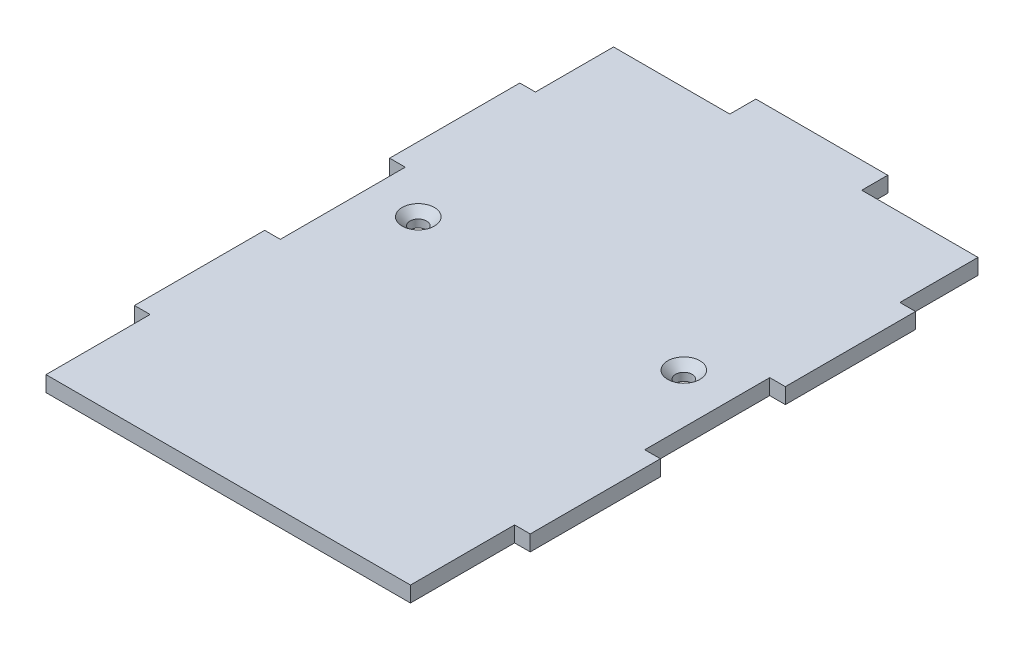
SolidWorks part; units mm, degrees
ref_plane "Front Plane" through (0, 0, 0) normal (0, 0, 1) x (1, 0, 0)
ref_plane "Top Plane" through (0, 0, 0) normal (0, 1, 0) x (1, 0, 0)
ref_plane "Right Plane" through (0, 0, 0) normal (1, 0, 0) x (0, 0, -1)
sketch "Sketch1" plane through (0, 0, 0) normal (0, 1, 0) x (1, 0, 0)
  line L0 (0, -57) -> (-35, -57)
  line L1 (-38, -57) -> (38, -57) construction
  line L2 (-38, -57) -> (-38, 57) construction
  line L3 (-38, 57) -> (38, 57) construction
  line L4 (38, -57) -> (38, 57) construction
  line L5 (0, 57) -> (0, -57)
  line L6 (-38, 0) -> (38, 0) construction
  line L7 (-35, -57) -> (-35, -37)
  line L8 (-35, -37) -> (-38, -37)
  line L9 (-38, -37) -> (-38, -12)
  line L10 (-38, -12) -> (-35, -12)
  line L11 (-35, -12) -> (-35, 12)
  line L12 (-35, 12) -> (-38, 12)
  line L13 (-38, 12) -> (-38, 37)
  line L14 (-38, 37) -> (-35, 37)
  line L15 (-35, 37) -> (-35, 52)
  line L16 (-35, 52) -> (-12.6667, 52)
  line L17 (-12.6667, 52) -> (-12.6667, 57)
  line L18 (-12.6667, 57) -> (0, 57)
  point P48 (0, 0)
  dimension "D1" = 114
  dimension "D2" = 76
  dimension "D3" = 3
  dimension "D4" = 20
  dimension "D5" = 25
  dimension "D6" = 20
  dimension "D7" = 5
  dimension "D8" = 25.3333
extrude "Boss-Extrude1" add sketch "Sketch1" along normal blind 3
mirror "Mirror1" about plane through (0, 3, -57) normal (-1, 0, 0) of "Boss-Extrude1"
sketch "Sketch2" plane through (0, 3, 0) normal (0, 1, 0) x (1, 0, 0)
  line L0 (-25.5, 5) -> (25.5, 5) construction
  line L1 (-35, -57) -> (35, -57) construction
  circle A0 centre (-25.5, 5) radius 1.6
  circle A1 centre (25.5, 5) radius 1.6
  point P2 (0, 5)
  dimension "D1" = 3.2
  dimension "D2" = 3.2
  dimension "D3" = 62
  dimension "D4" = 51
extrude "Cut-Extrude1" cut sketch "Sketch2" against normal through all
chamfer "Chamfer1" distance 1.5 2 edges at (25.5, 3, -3.4) (-25.5, 3, -3.4)
equation "\"3mm akryyli\"= 3mm"
equation "\"5mm akryyli\"= 5mm"
equation "\"D3@Sketch1\"=\"3mm akryyli\""
equation "\"D7@Sketch1\"=\"5mm akryyli\""
equation "\"D1@Boss-Extrude1\"=\"3mm akryyli\""
equation "\"D2@Sketch2\"=\"D1@Sketch2\""
